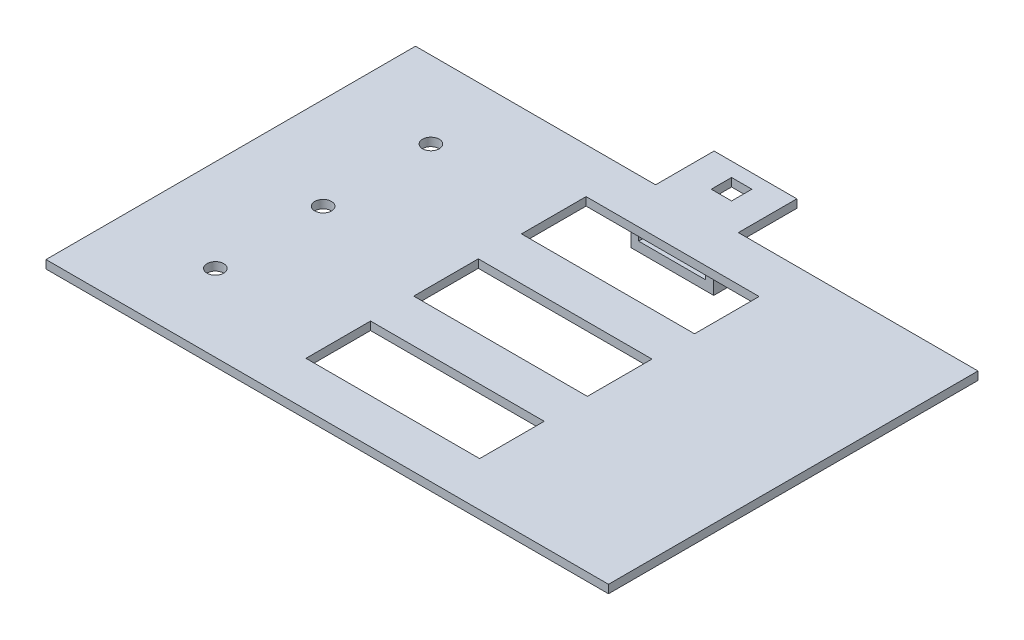
SolidWorks part; units mm, degrees
ref_plane "Front Plane" through (0, 0, 0) normal (0, 0, 1) x (1, 0, 0)
ref_plane "Top Plane" through (0, 0, 0) normal (0, 1, 0) x (1, 0, 0)
ref_plane "Right Plane" through (0, 0, 0) normal (1, 0, 0) x (0, 0, -1)
sketch "Sketch1" plane through (0, 0, 0) normal (0, 1, 0) x (1, 0, 0)
  line L1 (0, 0) -> (232.0036, 0)
  line L2 (0, 0) -> (0, 152.4)
  line L3 (0, 152.4) -> (232.0036, 152.4)
  line L4 (232.0036, 0) -> (232.0036, 152.4)
  dimension "D1" = 232.0036
  dimension "D2" = 152.4
extrude "Boss-Extrude1" add sketch "Sketch1" along normal blind 3.4036
sketch "Sketch2" plane through (0, 3.4036, 0) normal (0, 1, 0) x (1, 0, 0)
  line L1 (88.9, 133.858) -> (160.274, 133.858)
  line L2 (88.9, 133.858) -> (88.9, 107.2134)
  line L3 (88.9, 107.2134) -> (160.274, 107.2134)
  line L4 (160.274, 133.858) -> (160.274, 107.2134)
  line L5 (88.9, 89.408) -> (160.528, 89.408)
  line L6 (88.9, 89.408) -> (88.9, 62.7634)
  line L7 (88.9, 62.7634) -> (160.528, 62.7634)
  line L8 (160.528, 89.408) -> (160.528, 62.7634)
  line L10 (88.9, 44.958) -> (160.528, 44.958)
  line L11 (88.9, 44.958) -> (88.9, 18.3134)
  line L12 (88.9, 18.3134) -> (160.528, 18.3134)
  line L13 (160.528, 44.958) -> (160.528, 18.3134)
  line L14 (0, 0) -> (232.0036, 0) construction
  line L15 (0, 152.4) -> (0, 0) construction
  circle A0 centre (38.1, 120.65) radius 3.4417
  circle A1 centre (38.1, 76.2) radius 3.4417
  circle A2 centre (38.1, 31.75) radius 3.4417
  dimension "D7" = 6.8834
  dimension "D8" = 6.8834
  dimension "D9" = 6.8834
  dimension "D16" = 50.8
  dimension "D1" = 71.374
  dimension "D2" = 26.6446
  dimension "D3" = 26.6446
  dimension "D4" = 26.6446
  dimension "D5" = 71.628
  dimension "D6" = 71.628
  dimension "D10" = 44.45
  dimension "D11" = 31.75
  dimension "D12" = 44.45
  dimension "D13" = 38.1
  dimension "D14" = 0
  dimension "D15" = 0
  dimension "D17" = 50.8
  dimension "D18" = 50.8
  dimension "D19" = 13.208
  dimension "D20" = 13.208
  dimension "D21" = 13.208
extrude "Cut-Extrude1" cut sketch "Sketch2" against normal through all
sketch "Sketch3" plane through (0, 0, 0) normal (0, -1, 0) x (1, 0, 0)
  line L0 (232.0036, -152.4) -> (0, -152.4) construction
  line L1 (133.1595, -142.24) -> (99.0219, -142.24)
  line L2 (133.1595, -142.24) -> (133.1595, -156.21)
  line L3 (133.1595, -156.21) -> (99.0219, -156.21)
  line L4 (99.0219, -142.24) -> (99.0219, -156.21)
  line L5 (0, -152.4) -> (0, 0) construction
  dimension "D1" = 3.81
  dimension "D2" = 13.97
  dimension "D3" = 34.1376
  dimension "D4" = 99.0219
extrude "Boss-Extrude2" add sketch "Sketch3" along normal blind 13.97
sketch "Sketch4" plane through (0, 0, -156.21) normal (0, 0, -1) x (-1, 0, 0)
  line L1 (-129.7559, -3.4036) -> (-102.1715, -3.4036)
  line L2 (-129.7559, -3.4036) -> (-129.7559, -10.0584)
  line L3 (-129.7559, -10.0584) -> (-102.1715, -10.0584)
  line L4 (-102.1715, -3.4036) -> (-102.1715, -10.0584)
  line L6 (-133.1595, 0) -> (-99.0219, 0) construction
  line L7 (-133.1595, -13.97) -> (-133.1595, 0) construction
  dimension "D1" = 27.5844
  dimension "D2" = 6.6548
  dimension "D3" = 3.4036
  dimension "D4" = 3.4036
extrude "Cut-Extrude2" cut sketch "Sketch4" against normal blind 16.51
sketch "Sketch5" plane through (0, 0, -152.4) normal (0, 0, -1) x (-1, 0, 0)
  line L0 (-232.0036, 3.4036) -> (0, 3.4036) construction
  line L1 (-133.1595, 0) -> (-99.0219, 0)
  line L2 (-133.1595, 0) -> (-133.1595, 3.4036)
  line L3 (-133.1595, 3.4036) -> (-99.0219, 3.4036)
  line L4 (-99.0219, 0) -> (-99.0219, 3.4036)
  dimension "D1" = 0
extrude "Boss-Extrude3" add sketch "Sketch5" along normal blind 24.13
sketch "Sketch6" plane through (0, 3.4036, 0) normal (0, 1, 0) x (1, 0, 0)
  line L0 (133.1595, 176.53) -> (133.1595, 152.4) construction
  line L1 (112.0775, 170.688) -> (120.4595, 170.688)
  line L2 (112.0775, 170.688) -> (112.0775, 162.306)
  line L3 (112.0775, 162.306) -> (120.4595, 162.306)
  line L4 (120.4595, 170.688) -> (120.4595, 162.306)
  line L8 (99.0219, 156.21) -> (133.1595, 156.21) construction
  dimension "D1" = 8.382
  dimension "D2" = 8.382
  dimension "D3" = 12.7
  dimension "D4" = 6.096
extrude "Cut-Extrude3" cut sketch "Sketch6" against normal through all
